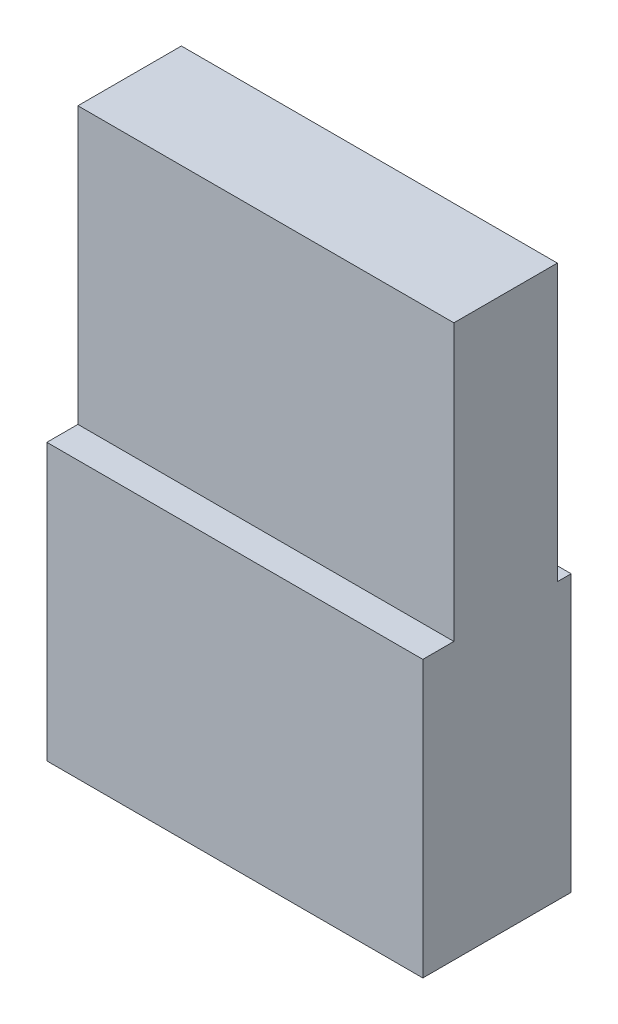
SolidWorks part; units mm, degrees
material "ABS"
ref_plane "Front Plane" through (0, 0, 0) normal (0, 0, 1) x (1, 0, 0)
ref_plane "Top Plane" through (0, 0, 0) normal (0, 1, 0) x (1, 0, 0)
ref_plane "Right Plane" through (0, 0, 0) normal (1, 0, 0) x (0, 0, -1)
sketch "Sketch1" plane through (0, 0, 0) normal (0, 1, 0) x (1, 0, 0)
  line L1 (-2.725, 1.075) -> (2.725, 1.075)
  line L2 (-2.725, 1.075) -> (-2.725, -1.075)
  line L3 (-2.725, -1.075) -> (2.725, -1.075)
  line L4 (2.725, 1.075) -> (2.725, -1.075)
  line L5 (-2.725, 1.075) -> (2.725, -1.075) construction
  line L6 (-2.725, -1.075) -> (2.725, 1.075) construction
  point P0 (0, 0)
  dimension "D1" = 5.45
  dimension "D2" = 2.15
extrude "Boss-Extrude1" add sketch "Sketch1" along normal blind 4
sketch "Sketch2" plane through (0, 4, 0) normal (0, 1, 0) x (1, 0, 0)
  line L0 (-2.725, 1.075) -> (-2.725, -1.075) construction
  line L1 (2.725, 0.875) -> (-2.725, 0.875)
  line L2 (2.725, 0.875) -> (2.725, -0.625)
  line L3 (2.725, -0.625) -> (-2.725, -0.625)
  line L4 (-2.725, 0.875) -> (-2.725, -0.625)
  line L5 (2.725, 0.875) -> (-2.725, -0.625) construction
  line L6 (2.725, -0.625) -> (-2.725, 0.875) construction
  line L7 (2.725, 1.075) -> (-2.725, 1.075) construction
  point P0 (0, 0.125)
  dimension "D1" = 1.5
  dimension "D2" = 0.2
extrude "Boss-Extrude2" add sketch "Sketch2" along normal blind 4
